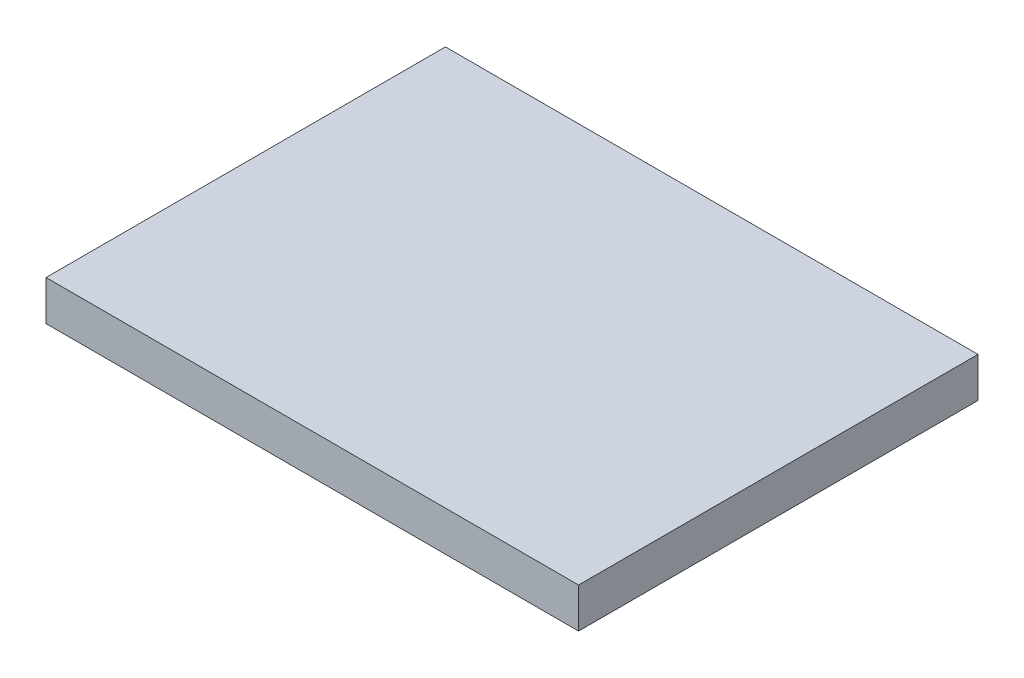
SolidWorks part; units mm, degrees
ref_plane "Front Plane" through (0, 0, 0) normal (0, 0, 1) x (1, 0, 0)
ref_plane "Top Plane" through (0, 0, 0) normal (0, 1, 0) x (1, 0, 0)
ref_plane "Right Plane" through (0, 0, 0) normal (1, 0, 0) x (0, 0, -1)
sketch "Sketch2" plane through (0, 0, 0) normal (0, 1, 0) x (1, 0, 0)
  line L1 (0, 0) -> (4000, 0)
  line L2 (0, 0) -> (0, 3000)
  line L3 (0, 3000) -> (4000, 3000)
  line L4 (4000, 0) -> (4000, 3000)
  dimension "D1" = 3000
  dimension "D2" = 4000
extrude "Boss-Extrude1" add sketch "Sketch2" along normal blind 300 contours L3 L4 L1 L2
